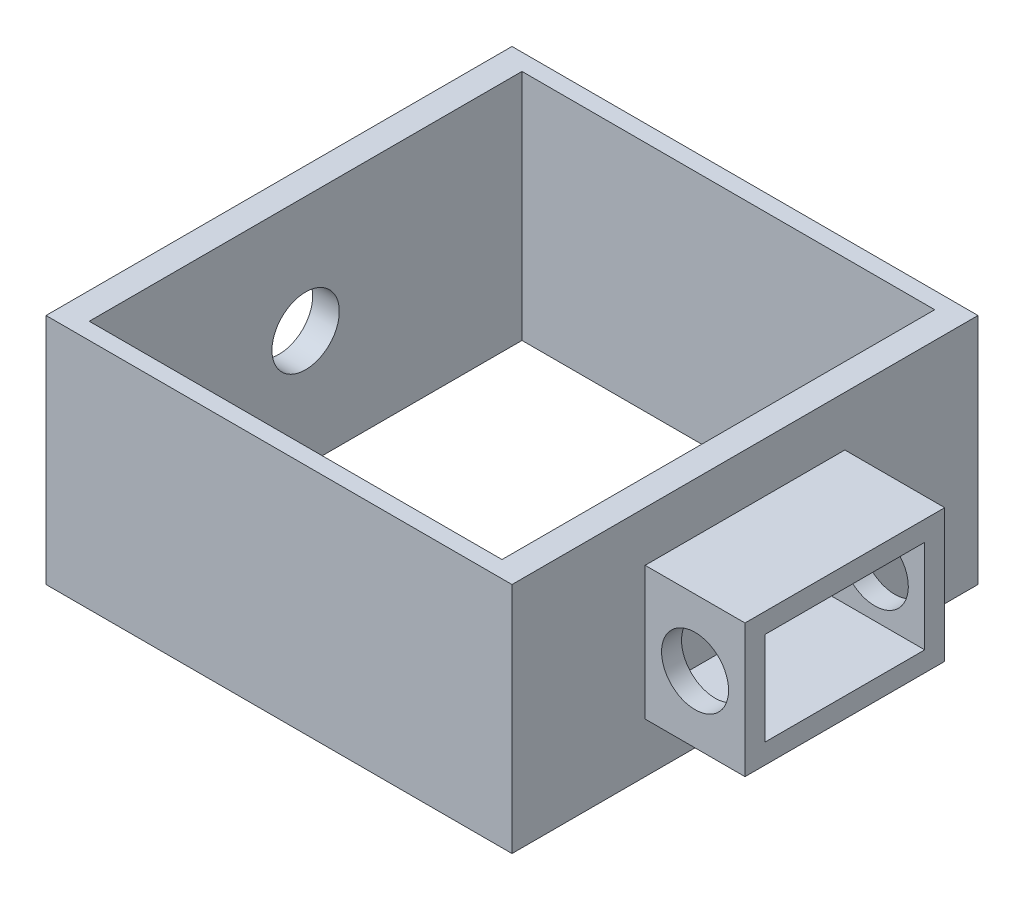
SolidWorks part; units mm, degrees
ref_plane "Front Plane" through (0, 0, 0) normal (0, 0, 1) x (1, 0, 0)
ref_plane "Top Plane" through (0, 0, 0) normal (0, 1, 0) x (1, 0, 0)
ref_plane "Right Plane" through (0, 0, 0) normal (1, 0, 0) x (0, 0, -1)
sketch "Sketch1" plane through (0, 0, 0) normal (0, 1, 0) x (1, 0, 0)
  line L1 (-35, 35) -> (35, 35)
  line L2 (-35, 35) -> (-35, -35)
  line L3 (-35, -35) -> (35, -35)
  line L4 (35, 35) -> (35, -35)
  line L5 (-35, 35) -> (35, -35) construction
  line L6 (-35, -35) -> (35, 35) construction
  point P0 (0, 0)
  dimension "D1" = 70
  dimension "D2" = 70
extrude "Boss-Extrude1" add sketch "Sketch1" along normal blind 35
sketch "Sketch2" plane through (0, 35, 0) normal (0, 1, 0) x (1, 0, 0)
  line L1 (-31, 32.5) -> (31, 32.5)
  line L2 (-31, 32.5) -> (-31, -32.5)
  line L3 (-31, -32.5) -> (31, -32.5)
  line L4 (31, 32.5) -> (31, -32.5)
  line L5 (-31, 32.5) -> (31, -32.5) construction
  line L6 (-31, -32.5) -> (31, 32.5) construction
  point P0 (0, 0)
  dimension "D1" = 62
  dimension "D2" = 65
extrude "Cut-Extrude1" cut sketch "Sketch2" against normal through all
sketch "Sketch3" plane through (-35, 0, 0) normal (-1, 0, 0) x (0, 0, 1)
  line L0 (-35, 17.5) -> (35, 17.5) construction
  line L1 (-35, 35) -> (-35, 0) construction
  line L2 (35, 35) -> (35, 0) construction
  line L3 (0, 35) -> (0, 0) construction
  line L4 (-35, 35) -> (35, 35) construction
  circle A0 centre (0, 17.5) radius 5.0568
extrude "Cut-Extrude2" cut sketch "Sketch3" against normal blind 15
sketch "Sketch4" plane through (35, 0, 0) normal (1, 0, 0) x (0, 0, -1)
  line L0 (-35, 17.5) -> (35, 17.5) construction
  line L1 (-35, 35) -> (-35, 0) construction
  line L2 (35, 35) -> (35, 0) construction
  line L4 (0, 0) -> (0, 35) construction
  line L5 (-35, 35) -> (35, 35) construction
  line L6 (-15, 27.5) -> (15, 27.5)
  line L7 (-15, 27.5) -> (-15, 7.5)
  line L8 (-15, 7.5) -> (15, 7.5)
  line L9 (15, 27.5) -> (15, 7.5)
  line L10 (-15, 27.5) -> (15, 7.5) construction
  line L11 (-15, 7.5) -> (15, 27.5) construction
  point P7 (0, 17.5)
  dimension "D1" = 30
  dimension "D2" = 20
extrude "Boss-Extrude2" add sketch "Sketch4" along normal blind 15
sketch "Sketch6" plane through (50, 0, 0) normal (1, 0, 0) x (0, 0, -1)
  line L0 (-15, 17.5) -> (15, 17.5) construction
  line L1 (-15, 27.5) -> (-15, 7.5) construction
  line L2 (15, 7.5) -> (15, 27.5) construction
  line L3 (0, 27.5) -> (0, 7.5) construction
  line L4 (15, 27.5) -> (-15, 27.5) construction
  line L5 (-15, 7.5) -> (15, 7.5) construction
  line L7 (-12, 24.5) -> (12, 24.5)
  line L8 (-12, 24.5) -> (-12, 10.5)
  line L9 (-12, 10.5) -> (12, 10.5)
  line L10 (12, 24.5) -> (12, 10.5)
  line L11 (-12, 24.5) -> (12, 10.5) construction
  line L12 (-12, 10.5) -> (12, 24.5) construction
  point P12 (0, 17.5)
  dimension "D1" = 24
  dimension "D2" = 14
extrude "Cut-Extrude3" cut sketch "Sketch6" against normal blind 15
sketch "Sketch7" plane through (0, 0, 15) normal (0, 0, 1) x (1, 0, 0)
  circle A0 centre (42.5, 17.5) radius 5.0339
extrude "Cut-Extrude4" cut sketch "Sketch7" against normal through all
